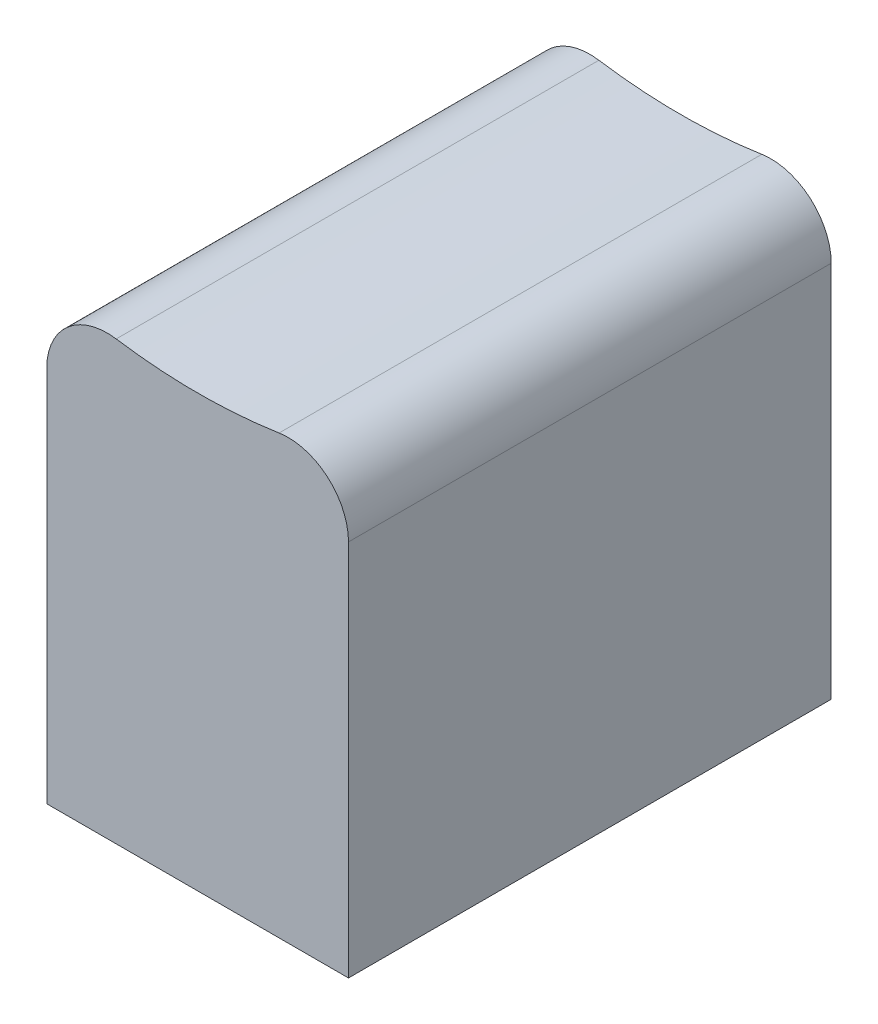
SolidWorks part; units mm, degrees
ref_plane "Front Plane" through (0, 0, 0) normal (0, 0, 1) x (1, 0, 0)
ref_plane "Top Plane" through (0, 0, 0) normal (0, 1, 0) x (1, 0, 0)
ref_plane "Right Plane" through (0, 0, 0) normal (1, 0, 0) x (0, 0, -1)
sketch "Sketch1" plane through (0, 0, 0) normal (0, 1, 0) x (1, 0, 0)
  line L1 (2, 0.8) -> (-2, 0.8)
  line L2 (2, 0.8) -> (2, -0.8)
  line L3 (2, -0.8) -> (-2, -0.8)
  line L4 (-2, 0.8) -> (-2, -0.8)
  line L5 (2, 0.8) -> (-2, -0.8) construction
  line L6 (2, -0.8) -> (-2, 0.8) construction
  point P0 (0, 0)
  dimension "D1" = 4
  dimension "D2" = 1.6
sketch "Sketch2" plane through (0, 0, 0) normal (0, 1, 0) x (1, 0, 0)
  line L1 (5, 8) -> (-5, 8)
  line L2 (5, 8) -> (5, -8)
  line L3 (5, -8) -> (-5, -8)
  line L4 (-5, 8) -> (-5, -8)
  line L5 (5, 8) -> (-5, -8) construction
  line L6 (5, -8) -> (-5, 8) construction
  point P0 (0, 0)
  dimension "D1" = 10
  dimension "D2" = 16
extrude "Boss-Extrude1" add sketch "Sketch2" along normal blind 15
sketch "Sketch4" plane through (0, 0, -8) normal (0, 0, -1) x (-1, 0, 0)
  line L0 (5, 15) -> (5, 0) construction
  line L1 (-5, 15) -> (5, 15) construction
  line L2 (5, 15) -> (-5, 15)
  arc A0 (-5, 15) -> (5, 15) centre (0, 32.2916) ccw
  point P3 (0, 14.2916)
  dimension "D1" = 18
extrude "Cut-Extrude1" cut sketch "Sketch4" against normal through all
fillet "Fillet1" radius 2 2 edges at (5, 15, 0) (-5, 15, 0)
extrude "Cut-Extrude3" cut sketch "Sketch1" along normal blind 12
